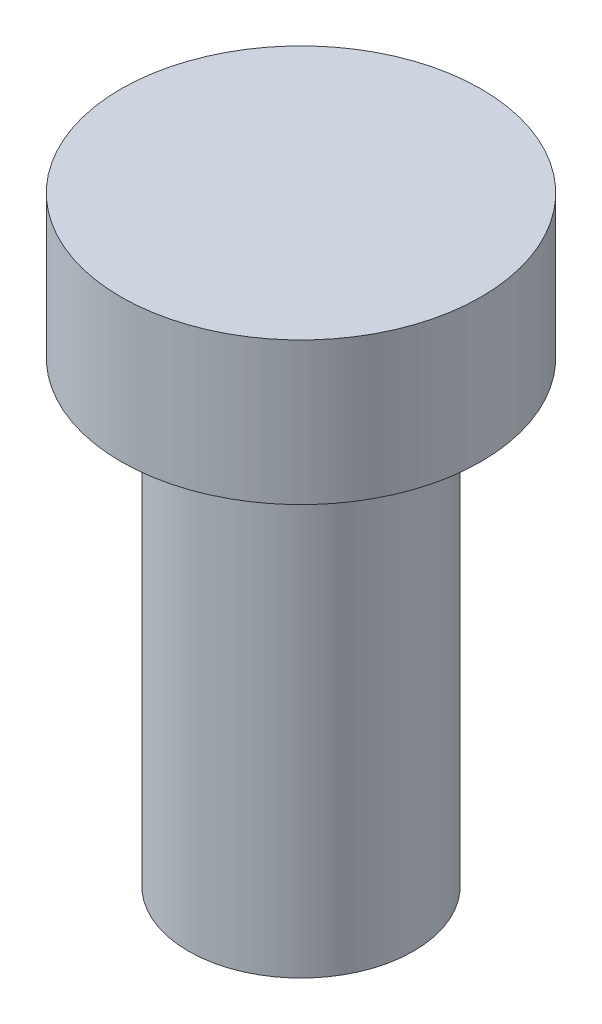
SolidWorks part; units mm, degrees
ref_plane "Plan de face" through (0, 0, 0) normal (0, 0, 1) x (1, 0, 0)
ref_plane "Plan de dessus" through (0, 0, 0) normal (0, 1, 0) x (1, 0, 0)
ref_plane "Plan de droite" through (0, 0, 0) normal (1, 0, 0) x (0, 0, -1)
sketch "Esquisse1" plane through (0, 0, 0) normal (0, 1, 0) x (1, 0, 0)
  circle A0 centre (0, 0) radius 2.4
  dimension "D1" = 4.8
extrude "Boss.-Extru.1" add sketch "Esquisse1" along normal blind 1.9
sketch "Esquisse2" plane through (0, 0, 0) normal (0, -1, 0) x (1, 0, 0)
  circle A0 centre (0, 0) radius 1.5
  dimension "D1" = 3
extrude "Boss.-Extru.2" add sketch "Esquisse2" along normal blind 6.1
